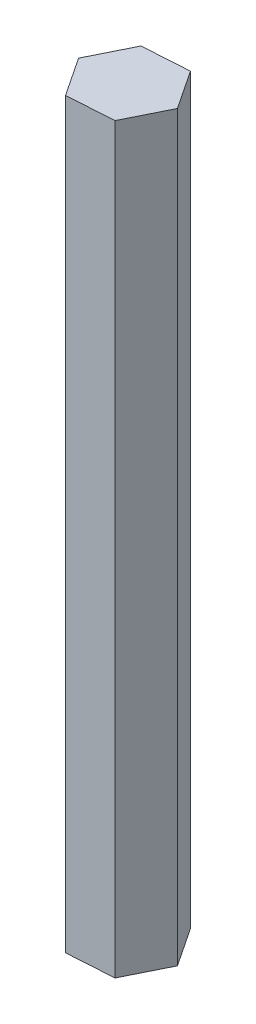
SolidWorks part; units mm, degrees
ref_plane "Front Plane" through (0, 0, 0) normal (0, 0, 1) x (1, 0, 0)
ref_plane "Top Plane" through (0, 0, 0) normal (0, 1, 0) x (1, 0, 0)
ref_plane "Right Plane" through (0, 0, 0) normal (1, 0, 0) x (0, 0, -1)
sketch "Sketch1" plane through (0, 0, 0) normal (0, 1, 0) x (1, 0, 0)
  line L1 (3.2599, 6.5678) -> (-4.0579, 6.1071)
  line L2 (-4.0579, 6.1071) -> (-7.3179, -0.4607)
  line L3 (-7.3179, -0.4607) -> (-3.2599, -6.5678)
  line L4 (-3.2599, -6.5678) -> (4.0579, -6.1071)
  line L5 (4.0579, -6.1071) -> (7.3179, 0.4607)
  line L6 (7.3179, 0.4607) -> (3.2599, 6.5678)
  circle A0 centre (0, 0) radius 6.35 construction
  dimension "D1" = 12.7
extrude "Boss-Extrude1" add sketch "Sketch1" along normal blind 116.84
